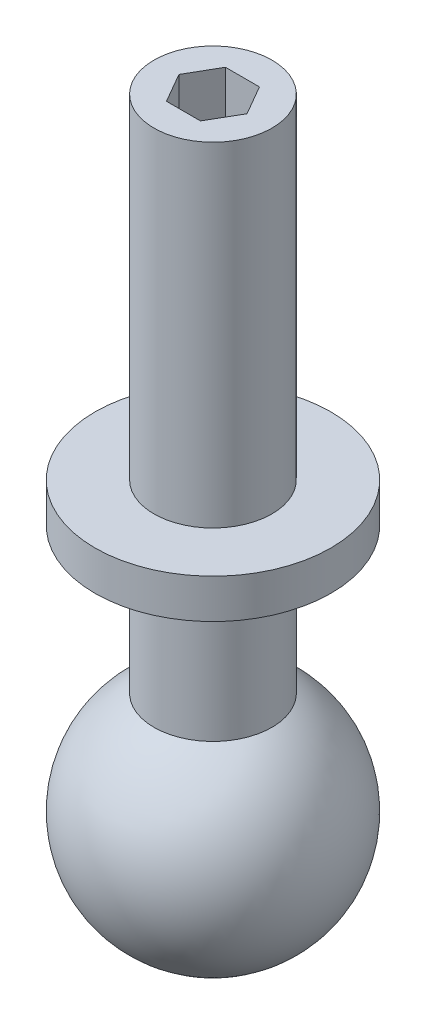
SolidWorks part; units mm, degrees
other "Cable Anchor Ball Stud"
other "Cable Anchor Ball Stud Left"
ref_plane "Front Plane" through (0, 0, 0) normal (0, 0, 1) x (1, 0, 0)
ref_plane "Top Plane" through (0, 0, 0) normal (0, 1, 0) x (1, 0, 0)
ref_plane "Right Plane" through (0, 0, 0) normal (1, 0, 0) x (0, 0, -1)
sketch3d "M3 neck and thread envelope sketch datum points"
  point P0 (-23.3827, -90, -19)
  point P1 (-13.3827, -90, -19)
  point P2 (-23.3827, -90, -9)
ref_plane "M3 neck and thread envelope sketch plane" through (0, -90, 0) normal (0, -1, 0) x (-1, 0, 0)
sketch "M3 neck and thread envelope sketch" plane through (0, -90, 0) normal (0, -1, 0) x (-1, 0, 0)
  circle A0 centre (23.3827, 19) radius 1.5
extrude "M3 neck and thread envelope" add sketch "M3 neck and thread envelope sketch" along normal blind 15.8 separate body
sketch3d "Six millimetre anchor ball axis line"
  line L0 (-23.3827, -90, -29) -> (-23.3827, -90, -9) construction
ref_axis "Six millimetre anchor ball axis" through (-23.3827, -90, -29) along (0, 0, 1)
sketch3d "Six millimetre anchor ball profile datum points"
  point P0 (-23.3827, -90, -19)
  point P1 (-13.3827, -90, -19)
  point P2 (-23.3827, -90, -9)
ref_plane "Six millimetre anchor ball profile plane" through (0, -90, 0) normal (0, -1, 0) x (-1, 0, 0)
sketch "Six millimetre anchor ball profile" plane through (0, -90, 0) normal (0, -1, 0) x (-1, 0, 0)
  line L0 (23.3827, 16) -> (23.3827, 22)
  arc A0 (23.3827, 22) -> (23.3827, 16) centre (23.3827, 19) ccw
revolve "Six millimetre anchor ball" add sketch "Six millimetre anchor ball profile" angle 360 about axis through (-23.3827, -90, -29) along (0, 0, 1)
sketch3d "Anchor seating collar sketch datum points"
  point P0 (-23.3827, -96.3, -19)
  point P1 (-13.3827, -96.3, -19)
  point P2 (-23.3827, -96.3, -9)
ref_plane "Anchor seating collar sketch plane" through (0, -96.3, 0) normal (0, -1, 0) x (-1, 0, 0)
sketch "Anchor seating collar sketch" plane through (0, -96.3, 0) normal (0, -1, 0) x (-1, 0, 0)
  circle A0 centre (23.3827, 19) radius 3
extrude "Anchor seating collar" add sketch "Anchor seating collar sketch" along normal blind 1
sketch3d "Anchor tail hex drive sketch datum points"
  point P0 (-23.3827, -105.9, -19)
  point P1 (-13.3827, -105.9, -19)
  point P2 (-23.3827, -105.9, -29)
ref_plane "Anchor tail hex drive sketch plane" through (0, -105.9, 0) normal (0, 1, 0) x (1, 0, 0)
sketch "Anchor tail hex drive sketch" plane through (0, -105.9, 0) normal (0, 1, 0) x (1, 0, 0)
  line L0 (-22.5167, 19) -> (-22.9497, 19.75)
  line L1 (-22.9497, 19.75) -> (-23.8157, 19.75)
  line L2 (-23.8157, 19.75) -> (-24.2487, 19)
  line L3 (-24.2487, 19) -> (-23.8157, 18.25)
  line L4 (-23.8157, 18.25) -> (-22.9497, 18.25)
  line L5 (-22.9497, 18.25) -> (-22.5167, 19)
  circle A0 centre (-23.3827, 19) radius 0.866 construction
extrude "Anchor tail hex drive" cut sketch "Anchor tail hex drive sketch" along normal blind 1.6
sketch3d "Mirror1 profile datum points"
  point P0 (0, 0, 0)
  point P1 (10, 0, 0)
  point P2 (0, 0, 10)
ref_plane "Mirror1 profile plane" through (0, 0, 0) normal (0, -1, 0) x (-1, 0, 0)
mirror "Mirror1" about plane through (0, 0, 0) normal (0, -1, 0) of bodies 104
delete or keep bodies "Remove1" type delete bodies bodies 104
